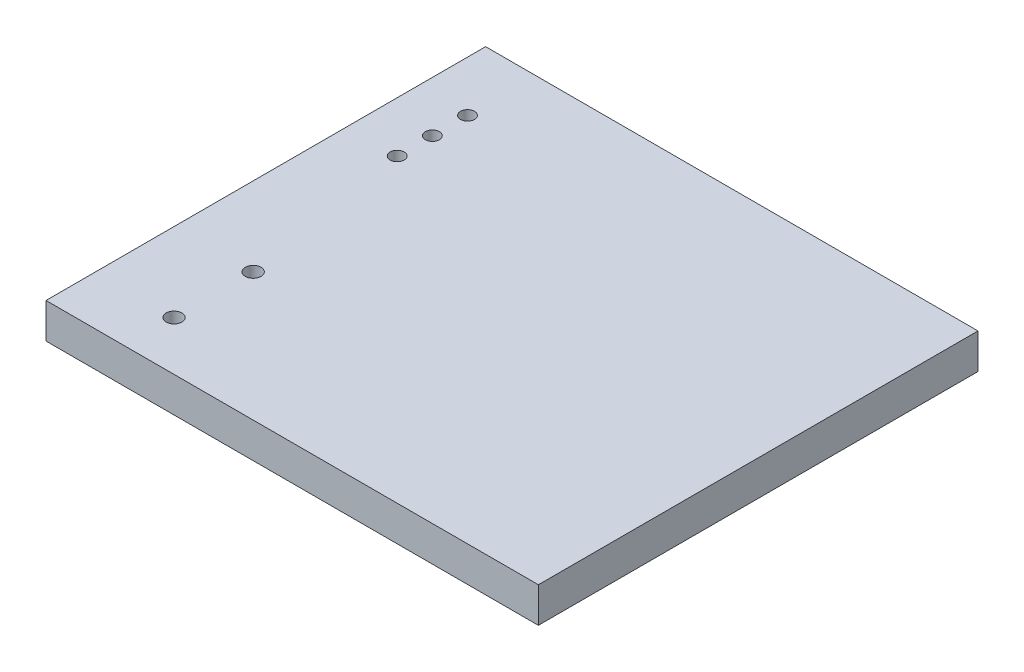
SolidWorks part; units mm, degrees
ref_plane "Front Plane" through (0, 0, 0) normal (0, 0, 1) x (1, 0, 0)
ref_plane "Top Plane" through (0, 0, 0) normal (0, 1, 0) x (1, 0, 0)
ref_plane "Right Plane" through (0, 0, 0) normal (1, 0, 0) x (0, 0, -1)
sketch "Sketch1" plane through (0, 0, 0) normal (0, 1, 0) x (1, 0, 0)
  line L1 (-14, -12.5) -> (14, -12.5)
  line L2 (-14, -12.5) -> (-14, 12.5)
  line L3 (-14, 12.5) -> (14, 12.5)
  line L4 (14, -12.5) -> (14, 12.5)
  line L5 (-14, -12.5) -> (14, 12.5) construction
  line L6 (-14, 12.5) -> (14, -12.5) construction
  point P0 (0, 0)
  dimension "D1" = 25
  dimension "D2" = 28
extrude "Boss-Extrude1" add sketch "Sketch1" along normal blind 2
sketch "Sketch2" plane through (0, 0, 0) normal (0, 1, 0) x (1, 0, 0)
  line L0 (-14, -12.5) -> (14, -12.5) construction
  line L2 (-14, 12.5) -> (-14, -12.5) construction
  circle A2 centre (-9.52, -5.2) radius 0.45
  circle A3 centre (-9.52, -9.7) radius 0.45
  dimension "D11" = 0.9
  dimension "D12" = 0.9
  dimension "D7" = 2.8
  dimension "D8" = 4.5
  dimension "D9" = 4.48
  dimension "D10" = 4.48
extrude "Cut-Extrude1" cut sketch "Sketch2" along normal blind 10
sketch "Sketch3" plane through (0, 0, 0) normal (0, 1, 0) x (1, 0, 0)
  line L0 (-14, 12.5) -> (-14, -12.5) construction
  line L3 (14, 12.5) -> (-14, 12.5) construction
  circle A3 centre (-11.13, 6.6) radius 0.4
  circle A4 centre (-11.13, 8.6) radius 0.4
  circle A5 centre (-11.13, 4.6) radius 0.4
  dimension "D16" = 0.8
  dimension "D17" = 0.8
  dimension "D18" = 0.8
  dimension "D10" = 3.9
  dimension "D11" = 2.87
  dimension "D12" = 2
  dimension "D13" = 2
  dimension "D14" = 2.87
  dimension "D15" = 2.87
extrude "Cut-Extrude2" cut sketch "Sketch3" along normal blind 2.5
